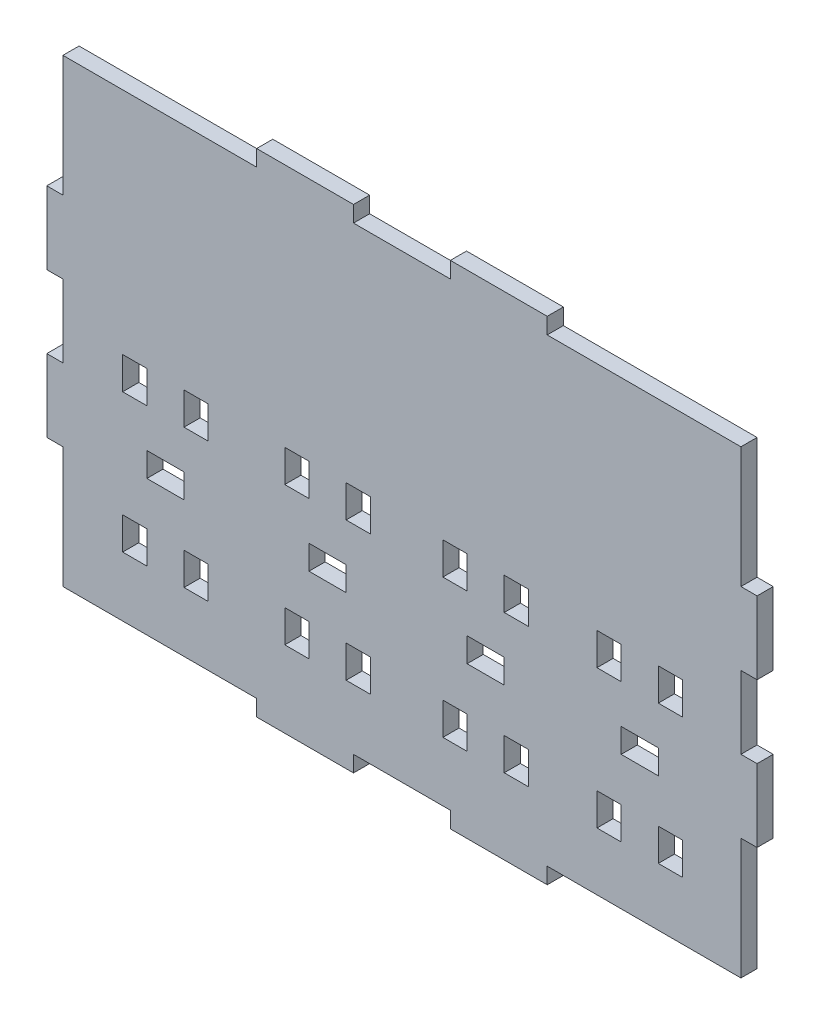
SolidWorks part; units mm, degrees
material "Acrylic (Medium-high impact)"
ref_plane "Front Plane" through (0, 0, 0) normal (0, 0, 1) x (1, 0, 0)
ref_plane "Top Plane" through (0, 0, 0) normal (0, 1, 0) x (1, 0, 0)
ref_plane "Right Plane" through (0, 0, 0) normal (1, 0, 0) x (0, 0, -1)
sketch "Sketch2" plane through (0, 0, 0) normal (0, 0, 1) x (1, 0, 0)
  line L0 (0, 0) -> (120, 0)
  line L1 (120, 0) -> (120, 10)
  line L2 (120, 10) -> (180, 10)
  line L3 (180, 10) -> (180, 0)
  line L4 (180, 0) -> (240, 0)
  line L5 (240, 0) -> (240, 10)
  line L6 (240, 10) -> (300, 10)
  line L7 (300, 10) -> (300, 0)
  line L8 (300, 0) -> (420, 0)
  line L9 (420, 0) -> (420, -75)
  line L10 (0, 0) -> (0, -75)
  line L11 (0, -285) -> (120, -285)
  line L12 (120, -285) -> (120, -295)
  line L13 (120, -295) -> (180, -295)
  line L14 (180, -295) -> (180, -285)
  line L15 (180, -285) -> (240, -285)
  line L16 (240, -285) -> (240, -295)
  line L17 (240, -295) -> (300, -295)
  line L18 (300, -295) -> (300, -285)
  line L19 (300, -285) -> (420, -285)
  line L20 (0, -75) -> (-10, -75)
  line L21 (-10, -75) -> (-10, -120)
  line L22 (-10, -120) -> (0, -120)
  line L23 (0, -120) -> (0, -165)
  line L24 (0, -165) -> (-10, -165)
  line L25 (-10, -165) -> (-10, -210)
  line L26 (-10, -210) -> (0, -210)
  line L27 (0, -210) -> (0, -285)
  line L28 (420, -75) -> (430, -75)
  line L29 (430, -75) -> (430, -120)
  line L30 (430, -120) -> (420, -120)
  line L31 (420, -120) -> (420, -165)
  line L32 (420, -165) -> (430, -165)
  line L33 (430, -165) -> (430, -210)
  line L34 (430, -210) -> (420, -210)
  line L35 (420, -210) -> (420, -285)
  line L52 (137.4167, -141.5614) -> (152.4167, -141.5614)
  line L53 (330.8152, -143.1187) -> (345.8152, -143.1187)
  line L54 (330.8152, -143.1187) -> (330.8152, -163.1187)
  line L55 (330.8152, -163.1187) -> (345.8152, -163.1187)
  line L56 (345.8152, -143.1187) -> (345.8152, -163.1187)
  line L57 (368.8152, -143.1187) -> (383.8152, -143.1187)
  line L58 (368.8152, -143.1187) -> (368.8152, -163.1187)
  line L59 (368.8152, -163.1187) -> (383.8152, -163.1187)
  line L60 (383.8152, -143.1187) -> (383.8152, -163.1187)
  line L61 (330.8152, -229.1187) -> (345.8152, -229.1187)
  line L62 (330.8152, -229.1187) -> (330.8152, -249.1187)
  line L63 (330.8152, -249.1187) -> (345.8152, -249.1187)
  line L64 (345.8152, -229.1187) -> (345.8152, -249.1187)
  line L69 (37, -142) -> (52, -142)
  line L70 (37, -142) -> (37, -162)
  line L71 (37, -162) -> (52, -162)
  line L72 (52, -142) -> (52, -162)
  line L73 (75, -142) -> (90, -142)
  line L74 (75, -142) -> (75, -162)
  line L75 (75, -162) -> (90, -162)
  line L76 (90, -142) -> (90, -162)
  line L77 (37, -228) -> (52, -228)
  line L78 (37, -228) -> (37, -248)
  line L79 (37, -248) -> (52, -248)
  line L80 (52, -228) -> (52, -248)
  line L81 (75, -228) -> (90, -228)
  line L82 (75, -228) -> (75, -248)
  line L83 (75, -248) -> (90, -248)
  line L84 (90, -228) -> (90, -248)
  line L85 (52, -186) -> (75, -186)
  line L86 (52, -186) -> (52, -201)
  line L87 (52, -201) -> (75, -201)
  line L88 (75, -186) -> (75, -201)
  line L89 (137.4167, -141.5614) -> (137.4167, -161.5614)
  line L90 (137.4167, -161.5614) -> (152.4167, -161.5614)
  line L91 (152.4167, -141.5614) -> (152.4167, -161.5614)
  line L92 (175.4167, -141.5614) -> (190.4167, -141.5614)
  line L93 (175.4167, -141.5614) -> (175.4167, -161.5614)
  line L94 (175.4167, -161.5614) -> (190.4167, -161.5614)
  line L95 (190.4167, -141.5614) -> (190.4167, -161.5614)
  line L96 (137.4167, -227.5614) -> (152.4167, -227.5614)
  line L97 (137.4167, -227.5614) -> (137.4167, -247.5614)
  line L98 (137.4167, -247.5614) -> (152.4167, -247.5614)
  line L99 (152.4167, -227.5614) -> (152.4167, -247.5614)
  line L100 (175.4167, -227.5614) -> (190.4167, -227.5614)
  line L101 (175.4167, -227.5614) -> (175.4167, -247.5614)
  line L102 (175.4167, -247.5614) -> (190.4167, -247.5614)
  line L103 (190.4167, -227.5614) -> (190.4167, -247.5614)
  line L104 (152.4167, -185.5614) -> (175.4167, -185.5614)
  line L105 (152.4167, -185.5614) -> (152.4167, -200.5614)
  line L106 (152.4167, -200.5614) -> (175.4167, -200.5614)
  line L107 (175.4167, -185.5614) -> (175.4167, -200.5614)
  line L108 (235.369, -142.2162) -> (250.369, -142.2162)
  line L109 (235.369, -142.2162) -> (235.369, -162.2162)
  line L110 (235.369, -162.2162) -> (250.369, -162.2162)
  line L111 (250.369, -142.2162) -> (250.369, -162.2162)
  line L112 (273.369, -142.2162) -> (288.369, -142.2162)
  line L113 (273.369, -142.2162) -> (273.369, -162.2162)
  line L114 (273.369, -162.2162) -> (288.369, -162.2162)
  line L115 (288.369, -142.2162) -> (288.369, -162.2162)
  line L116 (235.369, -228.2162) -> (250.369, -228.2162)
  line L117 (235.369, -228.2162) -> (235.369, -248.2162)
  line L118 (235.369, -248.2162) -> (250.369, -248.2162)
  line L119 (250.369, -228.2162) -> (250.369, -248.2162)
  line L120 (273.369, -228.2162) -> (288.369, -228.2162)
  line L121 (273.369, -228.2162) -> (273.369, -248.2162)
  line L122 (273.369, -248.2162) -> (288.369, -248.2162)
  line L123 (288.369, -228.2162) -> (288.369, -248.2162)
  line L124 (250.369, -186.2162) -> (273.369, -186.2162)
  line L125 (250.369, -186.2162) -> (250.369, -201.2162)
  line L126 (250.369, -201.2162) -> (273.369, -201.2162)
  line L127 (273.369, -186.2162) -> (273.369, -201.2162)
  line L128 (368.8152, -229.1187) -> (383.8152, -229.1187)
  line L129 (368.8152, -229.1187) -> (368.8152, -249.1187)
  line L130 (368.8152, -249.1187) -> (383.8152, -249.1187)
  line L131 (383.8152, -229.1187) -> (383.8152, -249.1187)
  line L132 (345.8152, -187.1187) -> (368.8152, -187.1187)
  line L133 (345.8152, -187.1187) -> (345.8152, -202.1187)
  line L134 (345.8152, -202.1187) -> (368.8152, -202.1187)
  line L135 (368.8152, -187.1187) -> (368.8152, -202.1187)
extrude "Boss-Extrude1" add sketch "Sketch2" along normal blind 10
